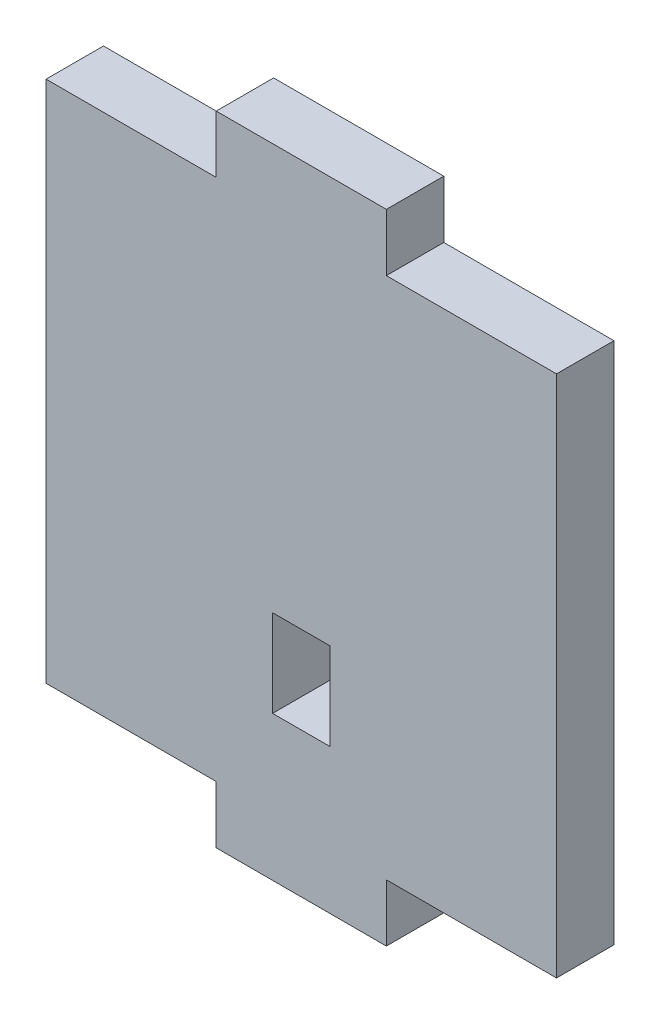
SolidWorks part; units mm, degrees
ref_plane "Front Plane" through (0, 0, 0) normal (0, 0, 1) x (1, 0, 0)
ref_plane "Top Plane" through (0, 0, 0) normal (0, 1, 0) x (1, 0, 0)
ref_plane "Right Plane" through (0, 0, 0) normal (1, 0, 0) x (0, 0, -1)
sketch "Sketch1" plane through (0, 0, 0) normal (0, 0, 1) x (1, 0, 0)
  line L0 (0, 95.5) -> (26.6667, 95.5) construction
  line L1 (0, 0) -> (80, 0)
  line L2 (0, 0) -> (0, 100)
  line L3 (0, 100) -> (80, 100)
  line L4 (80, 0) -> (80, 100)
  line L5 (0, 100) -> (80, 100)
  line L6 (0, 100) -> (0, 91)
  line L7 (0, 91) -> (80, 91)
  line L8 (80, 100) -> (80, 91)
  line L9 (26.6667, 95.5) -> (53.3333, 95.5) construction
  line L10 (26.6667, 100) -> (53.3333, 100)
  line L11 (26.6667, 100) -> (26.6667, 91)
  line L12 (26.6667, 91) -> (53.3333, 91)
  line L13 (53.3333, 100) -> (53.3333, 91)
  line L14 (53.3333, 95.5) -> (80, 95.5) construction
  line L15 (0, 50) -> (80, 50) construction
  line L16 (53.3333, 4.5) -> (80, 4.5) construction
  line L17 (26.6667, 4.5) -> (53.3333, 4.5) construction
  line L18 (0, 4.5) -> (26.6667, 4.5) construction
  line L19 (53.3333, 0) -> (53.3333, 9)
  line L20 (26.6667, 9) -> (53.3333, 9)
  line L21 (26.6667, 0) -> (26.6667, 9)
  line L22 (26.6667, 0) -> (53.3333, 0)
  line L23 (80, 0) -> (80, 9)
  line L24 (0, 9) -> (80, 9)
  line L25 (0, 0) -> (0, 9)
  line L26 (0, 0) -> (80, 0)
  line L27 (0, 0) -> (80, 0)
  line L28 (40, 100) -> (40, 0) construction
  line L29 (53.2031, 50) -> (53.2031, 36.3333) construction
  line L30 (35.5, 36.3333) -> (44.5, 36.3333)
  line L31 (35.5, 36.3333) -> (35.5, 22.6667)
  line L32 (35.5, 22.6667) -> (44.5, 22.6667)
  line L33 (44.5, 36.3333) -> (44.5, 22.6667)
  line L34 (53.2031, 36.3333) -> (53.2031, 22.6667) construction
  line L35 (53.2031, 22.6667) -> (53.2031, 9) construction
  point P33 (40, 36.3333)
  dimension "D1" = 80
  dimension "D2" = 100
  dimension "D3" = 9
  dimension "D4" = 9
extrude "Boss-Extrude1" add sketch "Sketch1" along normal blind 9 contours L2 L24 L20 L4 L7 | L13 L5 L11 L7 | L21 L1 L19 L20
